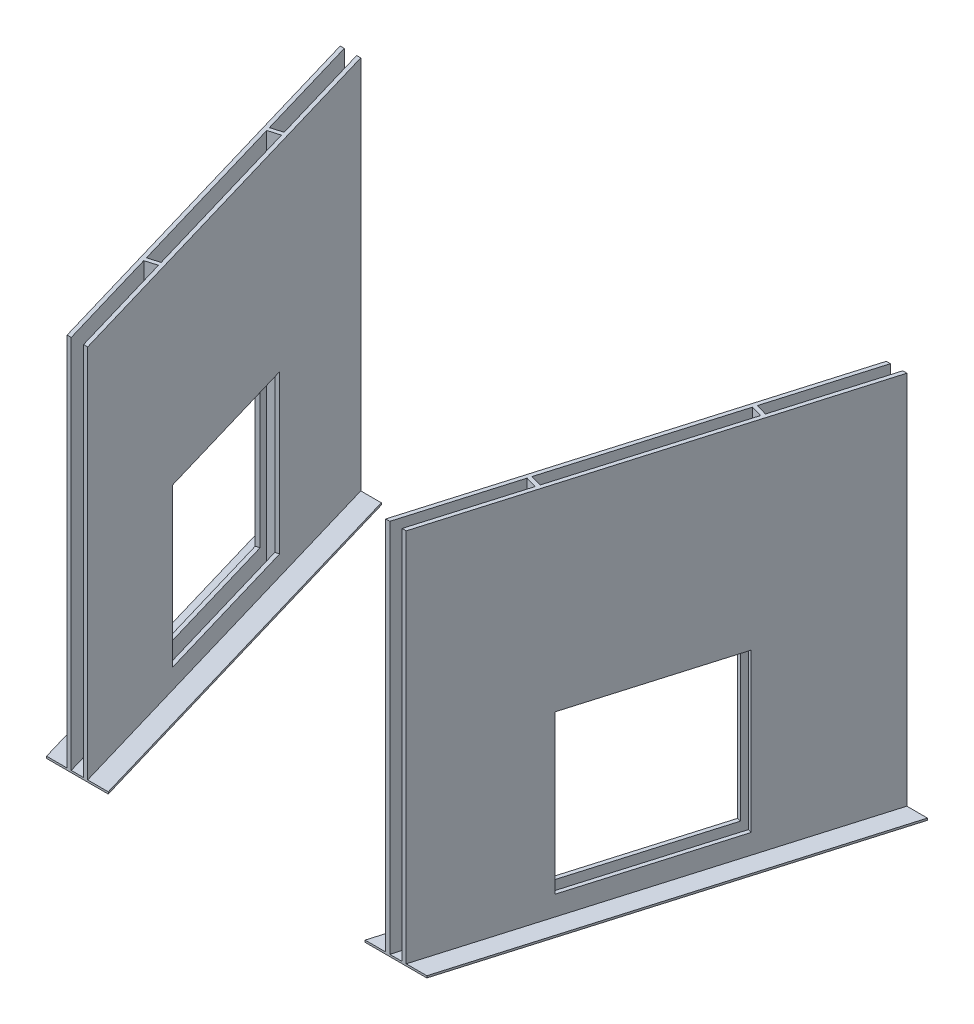
SolidWorks part; units mm, degrees
material "6061 Alloy"
ref_plane "Front Plane" through (0, 0, 0) normal (0, 0, 1) x (1, 0, 0)
ref_plane "Top Plane" through (0, 0, 0) normal (0, 1, 0) x (1, 0, 0)
ref_plane "Right Plane" through (0, 0, 0) normal (1, 0, 0) x (0, 0, -1)
sketch "Sketch1" plane through (0, 0, 0) normal (0, 1, 0) x (1, 0, 0)
  line L0 (-178.9535, 127) -> (-176.3059, 127) construction
  line L1 (-176.3059, 127) -> (-101.6, -127) construction
  line L2 (-101.6, -127) -> (-104.2476, -127) construction
  line L3 (-104.2476, -127) -> (-178.9535, 127) construction
  line L4 (101.6, -127) -> (104.2476, -127) construction
  line L5 (176.3059, 127) -> (101.6, -127) construction
  line L6 (178.9535, 127) -> (176.3059, 127) construction
  line L7 (104.2476, -127) -> (178.9535, 127) construction
  dimension "D1" = 2.54
  dimension "D2" = 2.54
  dimension "D3" = 101.6
  dimension "D4" = 101.6
  dimension "D5" = 254
  dimension "D6" = 254
  dimension "D7" = 74.7059
  dimension "D8" = 74.7059
  dimension "D9" = 2.6476
  dimension "D10" = 264.7583
  dimension "D11" = 127
  dimension "D12" = 127
sketch "Sketch2" plane through (0, 0, 0) normal (0, 1, 0) x (1, 0, 0)
  line L0 (-159.5898, 56.1895) -> (-152.2794, 58.3396)
  line L1 (-152.2794, 58.3396) -> (-151.5627, 55.9028)
  line L3 (-151.5627, 55.9028) -> (-158.8731, 53.7527)
  line L9 (-158.8731, 53.7527) -> (-159.5898, 56.1895)
  line L10 (-55, 0) -> (55, 0) construction
  line L11 (0, -55) -> (0, 55) construction
  line L20 (-125.9048, -58.3396) -> (-118.5944, -56.1895)
  line L36 (-125.9048, -58.3396) -> (-126.6215, -55.9028)
  line L37 (-176.3059, 127) -> (-101.6, -127) construction
  line L38 (119.3111, -53.7527) -> (118.5944, -56.1895)
  line L39 (-126.6215, -55.9028) -> (-119.3111, -53.7527)
  line L40 (-119.3111, -53.7527) -> (-118.5944, -56.1895)
  line L41 (126.6215, -55.9028) -> (119.3111, -53.7527)
  line L42 (125.9048, -58.3396) -> (126.6215, -55.9028)
  line L43 (125.9048, -58.3396) -> (118.5944, -56.1895)
  line L44 (158.8731, 53.7527) -> (159.5898, 56.1895)
  line L45 (151.5627, 55.9028) -> (158.8731, 53.7527)
  line L46 (152.2794, 58.3396) -> (151.5627, 55.9028)
  line L47 (159.5898, 56.1895) -> (152.2794, 58.3396)
  line L48 (-155.2179, 54.8277) -> (-139.0921, 0) construction
  line L49 (-139.0921, 0) -> (-122.9663, -54.8277) construction
  point P2 (-155.2179, 54.8277)
  dimension "D1" = 57.15
  dimension "D2" = 7.62
  dimension "D3" = 155.2179
  dimension "D4" = 2.54
  dimension "D5" = 2.54
  dimension "D6" = 57.15
extrude "Boss-Extrude2" add sketch "Sketch2" against normal blind 245.11
sketch "Sketch10" plane through (131.6731, 0, 38.7274) normal (0.9594, 0, 0.2822) x (0.2822, 0, -0.9594)
  line L1 (90.0471, -245.11) -> (-11.5529, -245.11) construction
  line L2 (90.0471, -245.11) -> (90.0471, -118.11) construction
  line L3 (90.0471, -118.11) -> (-11.5529, -118.11) construction
  line L4 (-11.5529, -245.11) -> (-11.5529, -118.11) construction
  line L6 (96.3971, -245.11) -> (98.9371, -245.11) construction
  line L7 (-17.9029, -245.11) -> (-17.9029, 0) construction
  line L8 (96.3971, -245.11) -> (96.3971, 0) construction
  point P7 (0, 0)
  point P12 (0, 0)
  point P13 (0, 0)
  point P14 (0, 0)
  point P15 (0, 0)
  point P16 (0, 0)
  point P17 (0, 0)
  dimension "D1" = 127
  dimension "D2" = 6.35
  dimension "D3" = 6.35
sketch "Sketch11" plane through (-131.6731, 0, 38.7274) normal (-0.9594, 0, 0.2822) x (0.2822, 0, 0.9594)
  line L1 (-90.0471, -245.11) -> (11.5529, -245.11) construction
  line L2 (-90.0471, -245.11) -> (-90.0471, -118.11) construction
  line L3 (-90.0471, -118.11) -> (11.5529, -118.11) construction
  line L4 (11.5529, -245.11) -> (11.5529, -118.11) construction
  line L5 (17.9029, -245.11) -> (17.9029, 0) construction
  line L6 (-98.9371, -245.11) -> (-96.3971, -245.11) construction
  line L7 (-96.3971, -245.11) -> (-96.3971, 0) construction
  point P5 (0, 0)
  point P7 (0, 0)
  point P9 (0, 0)
  dimension "D1" = 6.35
  dimension "D2" = 127
  dimension "D3" = 6.35
sketch "Sketch3" plane through (0, 0, 0) normal (0, 1, 0) x (1, 0, 0)
  line L0 (-152.2794, 58.3396) -> (-172.4737, 127)
  line L1 (-172.4737, 127) -> (-169.8261, 127)
  line L2 (-169.8261, 127) -> (-95.1202, -127)
  line L3 (-95.1202, -127) -> (-97.7678, -127)
  line L4 (-97.7678, -127) -> (-118.5944, -56.1895)
  line L5 (-152.2794, 58.3396) -> (-118.5944, -56.1895)
  line L6 (-101.6, -127) -> (-104.2476, -127) construction
  line L7 (-178.9535, 127) -> (-176.3059, 127) construction
  line L8 (-180.4164, 127) -> (-183.064, 127)
  line L9 (-183.064, 127) -> (-108.3581, -127)
  line L10 (-108.3581, -127) -> (-105.7105, -127)
  line L11 (-105.7105, -127) -> (-125.9048, -58.3396)
  line L12 (-125.9048, -58.3396) -> (-159.5898, 56.1895)
  line L13 (-159.5898, 56.1895) -> (-180.4164, 127)
  line L14 (0, -55) -> (0, 55) construction
  line L15 (159.5898, 56.1895) -> (180.4164, 127)
  line L16 (125.9048, -58.3396) -> (159.5898, 56.1895)
  line L17 (105.7105, -127) -> (125.9048, -58.3396)
  line L18 (108.3581, -127) -> (105.7105, -127)
  line L19 (183.064, 127) -> (108.3581, -127)
  line L20 (180.4164, 127) -> (183.064, 127)
  line L21 (152.2794, 58.3396) -> (118.5944, -56.1895)
  line L22 (97.7678, -127) -> (118.5944, -56.1895)
  line L23 (95.1202, -127) -> (97.7678, -127)
  line L24 (169.8261, 127) -> (95.1202, -127)
  line L25 (172.4737, 127) -> (169.8261, 127)
  line L26 (152.2794, 58.3396) -> (172.4737, 127)
  line L27 (-125.9048, -58.3396) -> (-118.5944, -56.1895) construction
  line L28 (-118.5944, -56.1895) -> (-119.3111, -53.7527) construction
  point P34 (0, 0)
  point P35 (-119.6664, -51.7802)
extrude "Boss-Extrude3" add sketch "Sketch3" against normal blind 245.11
sketch "Sketch4" plane through (-134.1099, 0, 39.4441) normal (-0.9594, 0, 0.2822) x (0.2822, 0, 0.9594)
  line L0 (91.2644, -245.11) -> (91.2644, 0) construction
  line L1 (-173.4939, -245.11) -> (91.2644, -245.11)
  line L2 (-173.4939, -245.11) -> (-173.4939, -243.84)
  line L3 (-173.4939, -243.84) -> (91.2644, -243.84)
  line L4 (91.2644, -245.11) -> (91.2644, -243.84)
  dimension "D1" = 1.27
extrude "Boss-Extrude4" add sketch "Sketch4" along normal blind 12.7
sketch "Sketch6" plane through (-121.9259, 0, 35.8606) normal (0.9594, 0, -0.2822) x (-0.2822, 0, -0.9594)
  line L0 (-152.4144, -245.11) -> (70.1849, -245.11) construction
  line L1 (-94.9997, -245.11) -> (169.7586, -245.11)
  line L2 (-94.9997, -245.11) -> (-94.9997, -243.84)
  line L3 (-94.9997, -243.84) -> (169.7586, -243.84)
  line L4 (169.7586, -245.11) -> (169.7586, -243.84)
  dimension "D1" = 1.27
extrude "Boss-Extrude5" add sketch "Sketch6" along normal blind 12.7 and the other way blind 12.7
sketch "Sketch7" plane through (121.9259, 0, 35.8606) normal (-0.9594, 0, -0.2822) x (-0.2822, 0, 0.9594)
  line L0 (-169.7586, -245.11) -> (94.9997, -245.11) construction
  line L1 (-169.7586, -245.11) -> (94.9997, -245.11)
  line L2 (-169.7586, -245.11) -> (-169.7586, -243.84)
  line L3 (-169.7586, -243.84) -> (94.9997, -243.84)
  line L4 (94.9997, -245.11) -> (94.9997, -243.84)
  point P6 (0, 0)
  point P9 (94.3733, -245.11)
  dimension "D1" = 1.27
extrude "Boss-Extrude6" add sketch "Sketch7" along normal blind 12.7 and the other way blind 12.7
sketch "Sketch8" plane through (134.1099, 0, 39.4441) normal (0.9594, 0, 0.2822) x (0.2822, 0, -0.9594)
  line L0 (173.4939, -245.11) -> (173.4939, 0) construction
  line L1 (-91.2644, -245.11) -> (173.4939, -245.11)
  line L2 (-91.2644, -245.11) -> (-91.2644, -243.84)
  line L3 (-91.2644, -243.84) -> (173.4939, -243.84)
  line L4 (173.4939, -245.11) -> (173.4939, -243.84)
  line L5 (-94.9997, -245.11) -> (173.4939, -245.11) construction
  line L6 (-91.2644, -243.84) -> (-91.2644, 0) construction
  dimension "D1" = 1.27
extrude "Boss-Extrude7" add sketch "Sketch8" along normal blind 12.7
sketch "Sketch13" plane through (-134.1099, 0, 39.4441) normal (-0.9594, 0, 0.2822) x (0.2822, 0, 0.9594)
  line L2 (-90.0471, -231.14) -> (-90.0471, -129.54)
  line L5 (-90.0471, -231.14) -> (11.5529, -231.14)
  line L6 (-90.0471, -129.54) -> (11.5529, -129.54)
  line L7 (11.5529, -129.54) -> (11.5529, -231.14)
  line L10 (11.5529, -245.11) -> (11.5529, -118.11) construction
  line L11 (-90.0471, -118.11) -> (11.5529, -118.11) construction
  line L12 (91.2644, -243.84) -> (-173.4939, -243.84) construction
  line L13 (-90.0471, -245.11) -> (-90.0471, -118.11) construction
  dimension "D1" = 12.7
  dimension "D2" = 114.3
extrude "Cut-Extrude1" cut sketch "Sketch13" against normal blind 12.7
sketch "Sketch14" plane through (0, 0, 0) normal (0, 1, 0) x (1, 0, 0)
  line L0 (-180.4164, 127) -> (-183.064, 127) construction
  line L1 (-183.064, 127) -> (-156.5882, 127)
  line L2 (-183.064, 127) -> (-183.064, 130.5835)
  line L4 (-156.5882, 127) -> (-156.5882, 130.5835)
  line L5 (-157.6421, 130.5835) -> (-82.9363, -123.4165) construction
  line L6 (0, -64.1735) -> (0, 64.1735) construction
  line L7 (156.5882, 127) -> (156.5882, 130.5835)
  line L8 (183.064, 130.5835) -> (156.5882, 130.5835)
  line L9 (183.064, 127) -> (183.064, 130.5835)
  line L10 (183.064, 127) -> (156.5882, 127)
  line L11 (-183.064, 130.5835) -> (-156.5882, 130.5835)
extrude "Cut-Extrude2" cut sketch "Sketch14" against normal through all
sketch "Sketch15" plane through (0, 0, 0) normal (0, 1, 0) x (1, 0, 0)
  line L0 (0, -64.1735) -> (0, 64.1735) construction
  line L1 (-95.1202, -127) -> (-121.596, -127)
  line L2 (-95.1202, -127) -> (-95.1202, -130.5835)
  line L3 (-95.1202, -130.5835) -> (-121.596, -130.5835)
  line L4 (-121.596, -127) -> (-121.596, -130.5835)
  line L5 (121.596, -127) -> (121.596, -130.5835)
  line L6 (95.1202, -130.5835) -> (121.596, -130.5835)
  line L7 (95.1202, -127) -> (95.1202, -130.5835)
  line L8 (95.1202, -127) -> (121.596, -127)
  line L9 (-120.5421, -130.5835) -> (-195.2479, 123.4165) construction
extrude "Cut-Extrude3" cut sketch "Sketch15" against normal through all
sketch "Sketch16" plane through (0, -245.11, 0) normal (0, -1, 0) x (1, 0, 0)
  line L1 (-82.9363, 123.4165) -> (-95.1202, 123.4165)
  line L3 (-81.8823, 127) -> (-95.1202, 127)
  line L4 (-95.1202, 123.4165) -> (-95.1202, 127)
  line L9 (-82.9363, 123.4165) -> (-81.8823, 127)
  line L11 (-82.9363, 123.4165) -> (-156.5882, -127) construction
  line L12 (0, -64.1735) -> (0, 64.1735) construction
  line L13 (82.9363, 123.4165) -> (81.8823, 127)
  line L14 (95.1202, 123.4165) -> (95.1202, 127)
  line L15 (81.8823, 127) -> (95.1202, 127)
  line L16 (82.9363, 123.4165) -> (95.1202, 123.4165)
extrude "Boss-Extrude8" add sketch "Sketch16" against normal blind 1.27
sketch "Sketch17" plane through (0, -245.11, 0) normal (0, -1, 0) x (1, 0, 0)
  line L0 (-195.2479, -123.4165) -> (-196.3019, -127)
  line L1 (-156.5882, -127) -> (-196.3019, -127)
  line L2 (-156.5882, -127) -> (-156.5882, -123.4165)
  line L3 (-156.5882, -123.4165) -> (-195.2479, -123.4165)
  line L5 (-195.2479, -123.4165) -> (-121.596, 127) construction
  line L6 (0, -64.1735) -> (0, 64.1735) construction
  line L7 (156.5882, -123.4165) -> (195.2479, -123.4165)
  line L8 (156.5882, -127) -> (156.5882, -123.4165)
  line L9 (156.5882, -127) -> (196.3019, -127)
  line L10 (195.2479, -123.4165) -> (196.3019, -127)
extrude "Boss-Extrude9" add sketch "Sketch17" against normal blind 1.27
sketch "Sketch18" plane through (121.9259, 0, 35.8606) normal (-0.9594, 0, -0.2822) x (-0.2822, 0, 0.9594)
  line L0 (-90.0471, -245.11) -> (-90.0471, -118.11) construction
  line L1 (-90.0471, -231.14) -> (11.5529, -231.14)
  line L2 (-90.0471, -231.14) -> (-90.0471, -129.54)
  line L3 (-90.0471, -129.54) -> (11.5529, -129.54)
  line L4 (11.5529, -231.14) -> (11.5529, -129.54)
  line L5 (11.5529, -245.11) -> (11.5529, -118.11) construction
  line L6 (156.1497, -243.84) -> (-66.4496, -243.84) construction
  dimension "D1" = 101.6
  dimension "D2" = 12.7
extrude "Cut-Extrude4" cut sketch "Sketch18" against normal through all
sketch "Sketch19" plane through (0, 0, 0) normal (1, 0, 0) x (0, 0, -1)
  line L0 (64.1735, 0) -> (-64.1735, 0) construction
  line L1 (-127, 0) -> (127, 0)
  line L2 (-127, 0) -> (-127, -2.54)
  line L3 (-127, -2.54) -> (127, -2.54)
  line L4 (127, 0) -> (127, -2.54)
  line L5 (127, -243.84) -> (127, 0) construction
  line L6 (-127, -243.84) -> (-127, 0) construction
  dimension "D1" = 2.54
extrude "Cut-Extrude5" cut sketch "Sketch19" against normal through all both and the other way through all
sketch "Sketch20" plane through (0, 0, 0) normal (0, 1, 0) x (1, 0, 0)
  line L0 (-196.3019, 127) -> (196.3019, 127)
  line L1 (196.3019, 127) -> (196.3019, 124.46)
  line L2 (196.3019, 124.46) -> (-196.3019, 124.46)
  line L3 (-196.3019, 124.46) -> (-196.3019, 127)
  line L4 (-134.8105, 0) -> (134.8105, 0) construction
  line L5 (-196.3019, -124.46) -> (-196.3019, -127)
  line L6 (196.3019, -124.46) -> (-196.3019, -124.46)
  line L7 (196.3019, -127) -> (196.3019, -124.46)
  line L8 (-196.3019, -127) -> (196.3019, -127)
  dimension "D1" = 2.54
extrude "Cut-Extrude6" cut sketch "Sketch20" against normal through all and the other way through all
